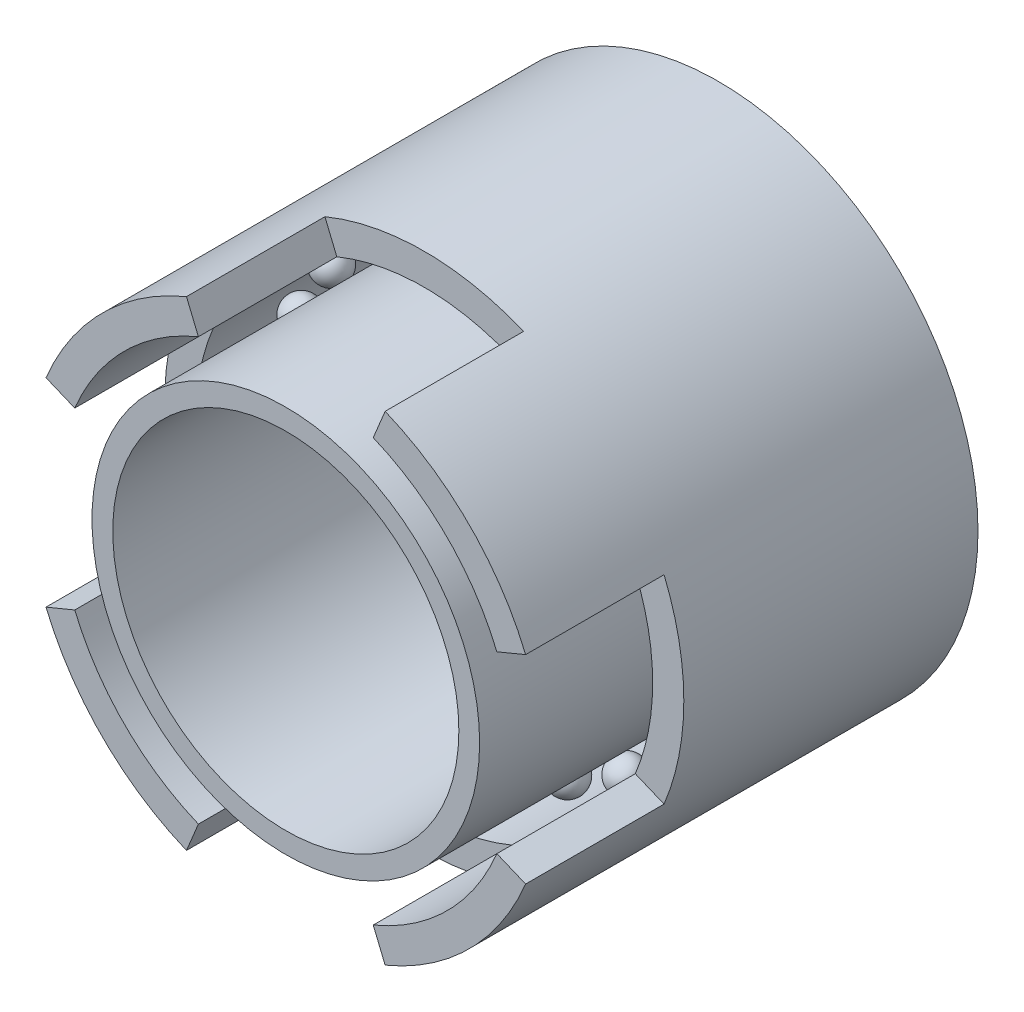
SolidWorks part; units mm, degrees
ref_plane "Front Plane" through (0, 0, 0) normal (0, 0, 1) x (1, 0, 0)
ref_plane "Top Plane" through (0, 0, 0) normal (0, 1, 0) x (1, 0, 0)
ref_plane "Right Plane" through (0, 0, 0) normal (1, 0, 0) x (0, 0, -1)
sketch "Sketch1" plane through (0, 0, 0) normal (0, 0, 1) x (1, 0, 0)
  circle A0 centre (0, 0) radius 19.05
  circle A1 centre (0, 0) radius 16.764
  circle A2 centre (0, 0) radius 14.224
  circle A3 centre (0, 0) radius 12.7
  point P7 (0, 0)
  dimension "D1" = 38.1
  dimension "D2" = 25.4
  dimension "D3" = 2.286
  dimension "D4" = 1.524
extrude "Boss-Extrude1" add sketch "Sketch1" against normal blind 31.75 contours A0 A1 | A2 A3
sketch "Sketch2" plane through (0, 0, 0) normal (0, 1, 0) x (1, 0, 0)
  line L0 (0, 0) -> (0, 31.75) construction
  line L1 (12.7, 31.75) -> (-12.7, 31.75) construction
  line L2 (0, 15.875) -> (-19.1843, 15.875) construction
  line L3 (0, 15.875) -> (19.0449, 15.875) construction
  line L4 (14.224, 15.875) -> (16.764, 15.875)
  arc A0 (16.764, 15.875) -> (14.224, 15.875) centre (15.494, 15.875) ccw
  point P1 (0, 0)
  dimension "D1" = 2.54
  dimension "D2" = 15.494
revolve "Revolve1" add sketch "Sketch2" angle 360 about L4
pattern_circular "CirPattern10" count 20 over 360 about axis through (0, 0, 0) along (0, 0, 1) of bodies 103
sketch "Sketch3" plane through (0, 0, 0) normal (0, 0, 1) x (1, 0, 0)
  line L0 (0, 0) -> (0, 19.05) construction
  line L1 (0, 0) -> (7.2901, 17.5999) construction
  line L2 (0, 0) -> (-7.2901, 17.5999) construction
  line L3 (-7.2901, 17.5999) -> (-6.4153, 15.4879)
  line L4 (7.2901, 17.5999) -> (6.4153, 15.4879)
  line L5 (17.5999, -7.2901) -> (15.4879, -6.4153)
  line L6 (17.5999, 7.2901) -> (15.4879, 6.4153)
  line L7 (-7.2901, -17.5999) -> (-6.4153, -15.4879)
  line L8 (7.2901, -17.5999) -> (6.4153, -15.4879)
  line L9 (-17.5999, 7.2901) -> (-15.4879, 6.4153)
  line L10 (-17.5999, -7.2901) -> (-15.4879, -6.4153)
  circle A0 centre (0, 0) radius 19.05 construction
  arc A1 (-7.2901, 17.5999) -> (7.2901, 17.5999) centre (0, 0) cw
  arc A2 (15.4879, 6.4153) -> (15.4879, -6.4153) centre (0, 0) cw
  arc A3 (-6.4153, 15.4879) -> (6.4153, 15.4879) centre (0, 0) cw
  circle A4 centre (0, 0) radius 16.764 construction
  arc A5 (17.5999, 7.2901) -> (17.5999, -7.2901) centre (0, 0) cw
  arc A6 (6.4153, -15.4879) -> (-6.4153, -15.4879) centre (0, 0) cw
  arc A7 (7.2901, -17.5999) -> (-7.2901, -17.5999) centre (0, 0) cw
  arc A8 (-15.4879, -6.4153) -> (-15.4879, 6.4153) centre (0, 0) cw
  arc A9 (-17.5999, -7.2901) -> (-17.5999, 7.2901) centre (0, 0) cw
  point P27 (0, 0)
  dimension "D1" = 45
  dimension "D2" = 22.5
  dimension "D3" = 4
extrude "Cut-Extrude1" cut sketch "Sketch3" against normal blind 10.16
